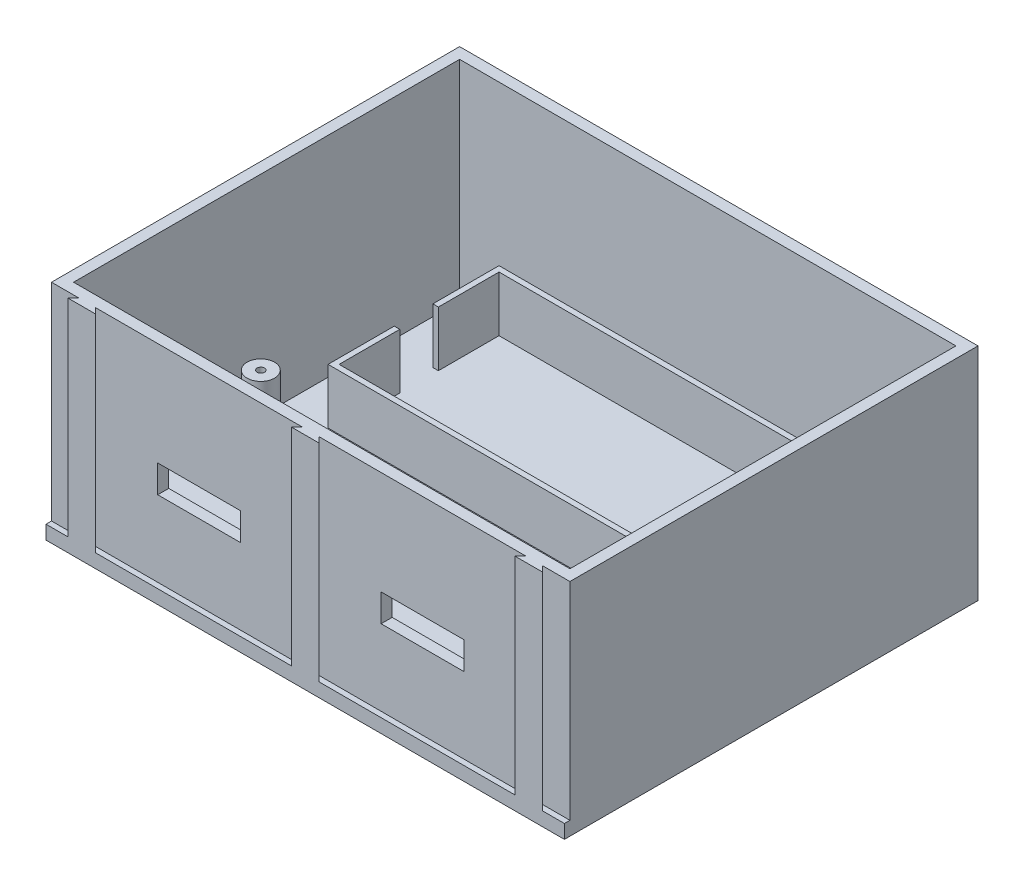
SolidWorks part; units mm, degrees
ref_plane "Płaszczyzna przednia" through (0, 0, 0) normal (0, 0, 1) x (1, 0, 0)
ref_plane "Płaszczyzna górna" through (0, 0, 0) normal (0, 1, 0) x (1, 0, 0)
ref_plane "Płaszczyzna prawa" through (0, 0, 0) normal (1, 0, 0) x (0, 0, -1)
sketch "Szkic1" plane through (0, 0, 0) normal (0, 1, 0) x (-1, 0, 0)
  line L1 (-303.2344, 978.2049) -> (-123.2344, 978.2049)
  line L8 (-303.2344, 978.2049) -> (-303.2344, 838.2049)
  line L9 (-303.2344, 838.2049) -> (-123.2344, 838.2049)
  line L10 (-123.2344, 838.2049) -> (-123.2344, 978.2049)
  line L11 (-159.8668, 927.7564) -> (-129.8668, 927.7564)
  line L12 (-129.8668, 927.7564) -> (-129.8668, 919.2564)
  line L13 (-129.8668, 919.2564) -> (-131.3668, 919.2564)
  line L14 (-131.3668, 919.2564) -> (-131.3668, 916.2564)
  line L30 (-131.3668, 916.2564) -> (-129.8668, 916.2564)
  line L48 (-300.1639, 903.0325) -> (-160.1639, 903.0325)
  line L49 (-160.1639, 903.0325) -> (-160.1639, 851.0325)
  line L50 (-160.1639, 851.0325) -> (-300.1639, 851.0325)
  line L51 (-300.1639, 851.0325) -> (-300.1639, 903.0325)
  line L52 (-284.2859, 973.5526) -> (-169.2859, 973.5526)
  line L53 (-284.2859, 973.5526) -> (-284.2859, 951.5526)
  line L54 (-284.2859, 951.5526) -> (-299.2859, 951.5526)
  line L55 (-299.2859, 951.5526) -> (-299.2859, 939.5526)
  line L56 (-299.2859, 939.5526) -> (-284.2859, 939.5526)
  line L57 (-284.2859, 939.5526) -> (-284.2859, 917.5526)
  line L58 (-284.2859, 917.5526) -> (-169.2859, 917.5526)
  line L59 (-169.2859, 917.5526) -> (-169.2859, 940.0526)
  line L60 (-169.2859, 940.0526) -> (-147.2859, 940.0526)
  line L61 (-147.2859, 940.0526) -> (-147.2859, 951.0526)
  line L62 (-147.2859, 951.0526) -> (-169.2859, 951.0526)
  line L63 (-129.8668, 916.2564) -> (-129.8668, 907.7564)
  line L64 (-169.2859, 951.0526) -> (-169.2859, 973.5526)
  line L65 (-129.8668, 907.7564) -> (-159.8668, 907.7564)
  line L66 (-159.8668, 907.7564) -> (-159.8668, 916.2564)
  line L67 (-159.8668, 916.2564) -> (-158.3668, 916.2564)
  line L68 (-158.3668, 916.2564) -> (-158.3668, 919.2564)
  line L69 (-158.3668, 919.2564) -> (-159.8668, 919.2564)
  line L70 (-159.8668, 919.2564) -> (-159.8668, 927.7564)
  line L71 (-168.2859, 952.0526) -> (-166.2859, 952.0526)
  line L72 (-285.2859, 938.5526) -> (-285.2859, 916.5526)
  line L74 (-166.2859, 976.5526) -> (-166.2859, 952.0526)
  line L75 (-285.2859, 952.5526) -> (-285.2859, 974.5526)
  line L76 (-299.2859, 945.5526) -> (-147.2859, 945.5526)
  line L77 (-168.2859, 939.0526) -> (-168.2859, 916.5526)
  line L80 (-168.2859, 952.0526) -> (-168.2859, 974.5526)
  line L81 (-168.2859, 974.5526) -> (-285.2859, 974.5526)
  line L82 (-287.2859, 976.5526) -> (-166.2859, 976.5526)
  line L83 (-285.2859, 952.5526) -> (-287.2859, 952.5526)
  line L84 (-287.2859, 952.5526) -> (-287.2859, 976.5526)
  line L86 (-285.2859, 938.5526) -> (-287.2859, 938.5526)
  line L87 (-287.2859, 938.5526) -> (-287.2859, 914.5526)
  line L88 (-287.2859, 914.5526) -> (-166.2859, 914.5526)
  line L89 (-166.2859, 914.5526) -> (-166.2859, 939.0526)
  line L90 (-168.2859, 939.0526) -> (-166.2859, 939.0526)
  line L92 (-168.2859, 916.5526) -> (-285.2859, 916.5526)
  circle A1 centre (-297.6639, 853.5325) radius 1.35
  circle A28 centre (-162.6639, 900.5325) radius 1.35
  circle A29 centre (-162.6639, 900.5325) radius 5
  circle A30 centre (-162.6639, 853.5325) radius 1.35
  circle A31 centre (-162.6639, 853.5325) radius 5
  circle A32 centre (-297.6639, 900.5325) radius 1.35
  circle A33 centre (-297.6639, 900.5325) radius 5
  circle A35 centre (-297.6639, 853.5325) radius 5
  circle A36 centre (-158.3668, 917.7564) radius 1.35
  circle A37 centre (-158.3668, 917.7564) radius 5
  circle A38 centre (-131.3668, 917.7564) radius 1.35
  circle A39 centre (-131.3668, 917.7564) radius 5
  dimension "D3" = 2.7
  dimension "D4" = 2.7
  dimension "D5" = 2.7
  dimension "D1" = 180
  dimension "D2" = 140
extrude "Dodanie-wyciągnięcie1" add sketch "Szkic1" along normal blind 4 contours L9 L10 L1 L8 A39 L63 L65 L66 A37 L70 L11 L12 A35 L51 A33 L48 A29 L49 A31 L50 L92 L77 L90 L89 L88 L87 L86 L72 L64 L62 L61 L60 L59 L58 L57 L56 L55 L54 L53 L52 L83 L84 L82 L74 | L76 L55 L56 L57 L58 L59 L60 L61 | L55 L76 L61 L62 L64 L52 L53 L54 | L12 A39 L63 L30 L14 A38 L13 | L63 A39 L12 L13 L14 A38 L30 | L14 A38 | L14 A38 | A39 L12 L11 L70 A37 L66 L65 L63 | L66 A37 L70 L69 L68 A36 L67 | L68 A36 | L68 A36 | L70 A37 L66 L67 L68 A36 L69 | L48 A29 L49 A28 | A28 | L49 A29 L48 | A35 L50 A31 L49 A29 L48 A33 L51 | L49 A31 L50 A30 | A30 | L50 A31 L49 | L50 A35 L51 A1 | A1 | L51 A35 L50 | L51 A33 L48 A32 | A32 | L48 A33 L51 | L77 L92 L72 L86 L87 L88 L89 L90 | L84 L83 L75 L81 L80 L71 L74 L82
sketch "Szkic6" plane through (0, 4, 0) normal (0, 1, 0) x (1, 0, 0)
  line L0 (123.2344, -838.2049) -> (303.2344, -838.2049)
  line L1 (123.2344, -838.2049) -> (123.2344, -978.2049)
  line L2 (123.2344, -978.2049) -> (303.2344, -978.2049)
  line L3 (303.2344, -978.2049) -> (303.2344, -838.2049)
  line L4 (266.602, -888.6534) -> (296.602, -888.6534)
  line L5 (296.602, -888.6534) -> (296.602, -897.1534)
  line L6 (296.602, -897.1534) -> (295.102, -897.1534)
  line L7 (295.102, -897.1534) -> (295.102, -900.1534)
  line L8 (295.102, -900.1534) -> (296.602, -900.1534)
  line L9 (126.3049, -913.3773) -> (266.3049, -913.3773)
  line L10 (266.3049, -913.3773) -> (266.3049, -965.3773)
  line L11 (266.3049, -965.3773) -> (126.3049, -965.3773)
  line L12 (126.3049, -965.3773) -> (126.3049, -913.3773)
  line L13 (142.183, -842.8572) -> (257.183, -842.8572)
  line L14 (142.183, -842.8572) -> (142.183, -864.8572)
  line L15 (142.183, -864.8572) -> (127.183, -864.8572)
  line L16 (127.183, -864.8572) -> (127.183, -876.8572)
  line L17 (127.183, -876.8572) -> (142.183, -876.8572)
  line L18 (142.183, -876.8572) -> (142.183, -898.8572)
  line L19 (142.183, -898.8572) -> (257.183, -898.8572)
  line L20 (257.183, -898.8572) -> (257.183, -876.3572)
  line L21 (257.183, -876.3572) -> (279.183, -876.3572)
  line L22 (279.183, -876.3572) -> (279.183, -865.3572)
  line L23 (279.183, -865.3572) -> (257.183, -865.3572)
  line L24 (296.602, -900.1534) -> (296.602, -908.6534)
  line L25 (257.183, -865.3572) -> (257.183, -842.8572)
  line L26 (296.602, -908.6534) -> (266.602, -908.6534)
  line L27 (266.602, -908.6534) -> (266.602, -900.1534)
  line L28 (266.602, -900.1534) -> (268.102, -900.1534)
  line L29 (268.102, -900.1534) -> (268.102, -897.1534)
  line L30 (268.102, -897.1534) -> (266.602, -897.1534)
  line L31 (266.602, -897.1534) -> (266.602, -888.6534)
  line L32 (258.183, -864.3572) -> (260.183, -864.3572)
  line L33 (141.183, -877.8572) -> (141.183, -899.8572)
  line L34 (260.183, -839.8572) -> (260.183, -864.3572)
  line L35 (141.183, -863.8572) -> (141.183, -841.8572)
  line L36 (127.183, -870.8572) -> (279.183, -870.8572)
  line L37 (258.183, -877.3572) -> (258.183, -899.8572)
  line L38 (258.183, -864.3572) -> (258.183, -841.8572)
  line L39 (258.183, -841.8572) -> (141.183, -841.8572)
  line L40 (139.183, -839.8572) -> (260.183, -839.8572)
  line L41 (141.183, -863.8572) -> (139.183, -863.8572)
  line L42 (139.183, -863.8572) -> (139.183, -839.8572)
  line L43 (141.183, -877.8572) -> (139.183, -877.8572)
  line L44 (139.183, -877.8572) -> (139.183, -901.8572)
  line L45 (139.183, -901.8572) -> (260.183, -901.8572)
  line L46 (260.183, -901.8572) -> (260.183, -877.3572)
  line L47 (258.183, -877.3572) -> (260.183, -877.3572)
  line L48 (258.183, -899.8572) -> (141.183, -899.8572)
  circle A0 centre (128.8049, -962.8773) radius 1.35
  circle A1 centre (263.8049, -915.8773) radius 1.35
  circle A2 centre (263.8049, -915.8773) radius 5
  circle A3 centre (263.8049, -962.8773) radius 1.35
  circle A4 centre (263.8049, -962.8773) radius 5
  circle A5 centre (128.8049, -915.8773) radius 1.35
  circle A6 centre (128.8049, -915.8773) radius 5
  circle A7 centre (128.8049, -962.8773) radius 5
  circle A8 centre (268.102, -898.6534) radius 1.35
  circle A9 centre (268.102, -898.6534) radius 5
  circle A10 centre (295.102, -898.6534) radius 1.35
  circle A11 centre (295.102, -898.6534) radius 5
  dimension "D3" = 2.7
  dimension "D4" = 2.7
  dimension "D5" = 2.7
  dimension "D1" = 180
  dimension "D2" = 140
extrude "Dodanie-wyciągnięcie2" add sketch "Szkic6" along normal blind 20 contours L45 L46 L47 L37 L48 L33 L43 L44 | L35 L39 L38 L32 L34 L40 L42 L41 | A6 | A7 | A2 | A4 | A3 | A1 | A5 | A0 | A9 | A8 | A11 | A10
sketch "Szkic13" plane through (0, 0, 0) normal (0, -1, 0) x (1, 0, 0)
  line L0 (119.2344, 982.2049) -> (307.2344, 982.2049)
  line L1 (123.2344, 978.2049) -> (303.2344, 978.2049)
  line L2 (123.2344, 978.2049) -> (123.2344, 838.2049)
  line L3 (123.2344, 838.2049) -> (303.2344, 838.2049)
  line L4 (303.2344, 978.2049) -> (303.2344, 838.2049)
  line L9 (119.2344, 982.2049) -> (119.2344, 834.2049)
  line L10 (119.2344, 834.2049) -> (307.2344, 834.2049)
  line L11 (307.2344, 982.2049) -> (307.2344, 834.2049)
  dimension "D1" = 4
  dimension "D2" = 4
  dimension "D4" = 4
  dimension "D5" = 148
extrude "Dodanie-wyciągnięcie3" add sketch "Szkic13" against normal blind 80
sketch "Szkic14" plane through (0, 0, 982.2049) normal (0, 0, 1) x (1, 0, 0)
  line L1 (119.2344, 80) -> (119.2344, 0) construction
  line L3 (307.2344, 80) -> (307.2344, 0) construction
  line L5 (307.2344, 0) -> (119.2344, 0)
  line L6 (119.2344, 0) -> (119.2344, 5)
  line L7 (119.2344, 5) -> (307.2344, 5)
  line L8 (307.2344, 5) -> (307.2344, 0)
extrude "Dodanie-wyciągnięcie4" add sketch "Szkic14" along normal blind 2
sketch "Szkic15" plane through (0, 5, 0) normal (0, 1, 0) x (1, 0, 0)
  line L0 (119.2344, -982.2049) -> (129.2344, -982.2049)
  line L1 (307.2344, -982.2049) -> (119.2344, -982.2049) construction
  line L2 (307.2344, -982.2049) -> (297.2344, -982.2049)
  line L3 (297.2344, -982.2049) -> (299.2876, -984.2049)
  line L4 (307.2344, -984.2049) -> (119.2344, -984.2049) construction
  line L5 (299.2876, -984.2049) -> (289.2876, -984.2049)
  line L6 (289.2876, -984.2049) -> (291.2876, -982.2049)
  line L7 (307.2344, -982.2049) -> (119.2344, -982.2049) construction
  line L8 (291.2876, -982.2049) -> (297.2344, -982.2049)
  line L9 (129.2344, -982.2049) -> (127.2344, -984.2049)
  line L10 (127.2344, -984.2049) -> (137.2344, -984.2049)
  line L11 (137.2344, -984.2049) -> (135.2344, -982.2049)
  line L12 (135.2344, -982.2049) -> (129.2344, -982.2049)
  line L19 (213.261, -984.2049) -> (218.261, -984.2049)
  line L20 (213.261, -984.2049) -> (208.261, -984.2049)
  line L21 (208.261, -984.2049) -> (210.261, -982.2049)
  line L22 (218.261, -984.2049) -> (216.261, -982.2049)
  line L23 (216.261, -982.2049) -> (210.261, -982.2049)
  dimension "D1" = 10
  dimension "D2" = 10
  dimension "D3" = 10
  dimension "D4" = 10
extrude "Dodanie-wyciągnięcie5" add sketch "Szkic15" along normal up to vertex (75 mm away)
sketch "Szkic17" plane through (0, 0, 982.2049) normal (0, 0, 1) x (1, 0, 0)
  line L0 (210.261, 80) -> (216.261, 80)
  line L1 (210.261, 5) -> (135.2344, 5)
  line L2 (210.261, 5) -> (210.261, 80)
  line L3 (210.261, 80) -> (135.2344, 80)
  line L4 (135.2344, 5) -> (135.2344, 80)
  line L5 (213.261, 80) -> (213.261, 5)
  line L6 (268.7743, 42.5) -> (238.7743, 42.5)
  line L7 (157.7477, 42.5) -> (187.7477, 42.5)
  line L8 (157.7477, 42.5) -> (157.7477, 32.5)
  line L9 (157.7477, 32.5) -> (187.7477, 32.5)
  line L10 (187.7477, 42.5) -> (187.7477, 32.5)
  line L11 (268.7743, 42.5) -> (268.7743, 32.5)
  line L12 (268.7743, 32.5) -> (238.7743, 32.5)
  line L13 (238.7743, 42.5) -> (238.7743, 32.5)
  line L14 (216.261, 80) -> (291.2876, 80)
  line L15 (291.2876, 5) -> (291.2876, 80)
  line L16 (216.261, 5) -> (291.2876, 5)
  line L17 (216.261, 5) -> (216.261, 80)
  dimension "D1" = 10
  dimension "D2" = 30
extrude "Wytnij-wyciągnięcie1" cut sketch "Szkic17" against normal up to next contours L10 L7 L8 L9 | L17 L16 L15 L14 L13 L6 L11 L12
